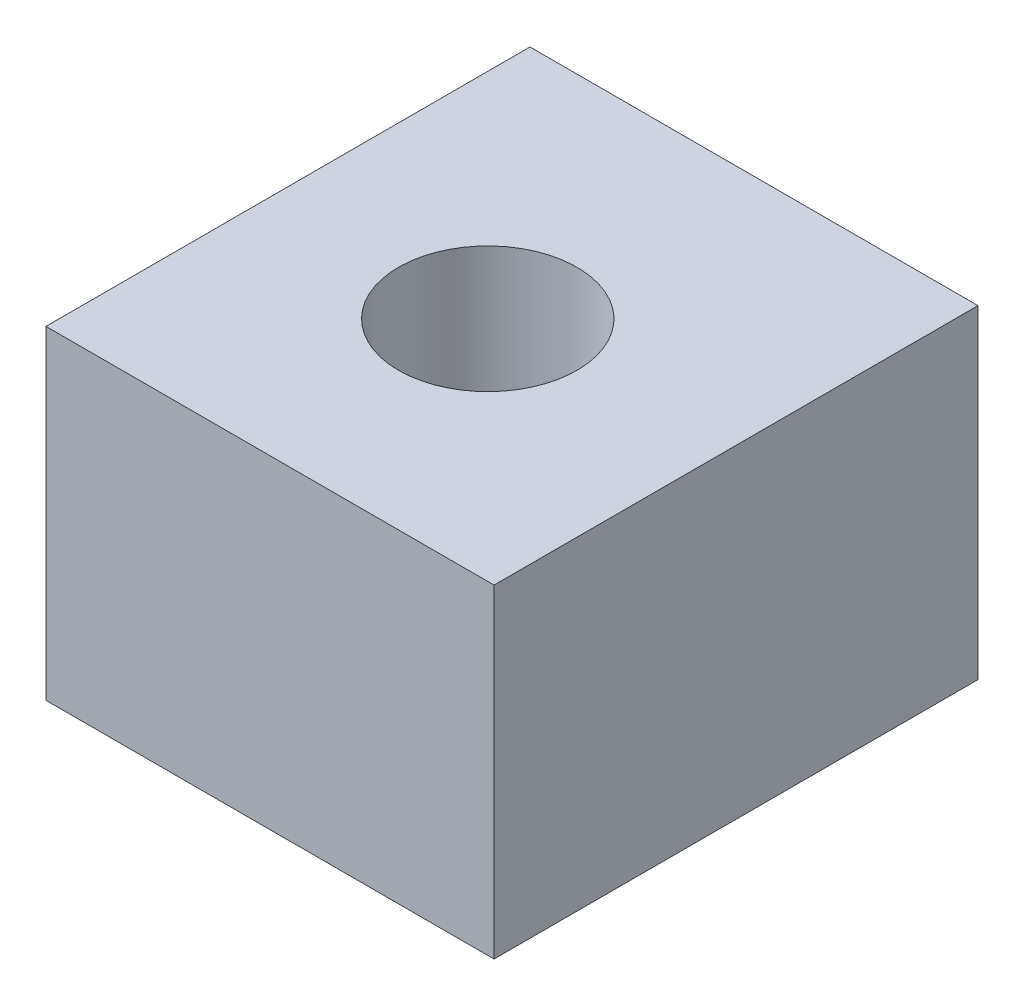
SolidWorks part; units mm, degrees
ref_plane "Front Plane" through (0, 0, 0) normal (0, 0, 1) x (1, 0, 0)
ref_plane "Top Plane" through (0, 0, 0) normal (0, 1, 0) x (1, 0, 0)
ref_plane "Right Plane" through (0, 0, 0) normal (1, 0, 0) x (0, 0, -1)
sketch "Sketch1" plane through (0, 0, 0) normal (0, 0, 1) x (1, 0, 0)
  line L1 (0, 0) -> (86.5324, 0)
  line L2 (0, 0) -> (0, -62.5552)
  line L3 (0, -62.5552) -> (86.5324, -62.5552)
  line L4 (86.5324, 0) -> (86.5324, -62.5552)
extrude "Boss-Extrude1" add sketch "Sketch1" along normal blind 93.472
sketch "Sketch2" plane through (0, 0, 0) normal (0, 1, 0) x (1, 0, 0)
  circle A0 centre (41.3919, -49.5413) radius 17.242
extrude "Cut-Extrude1" cut sketch "Sketch2" against normal blind 93.472
